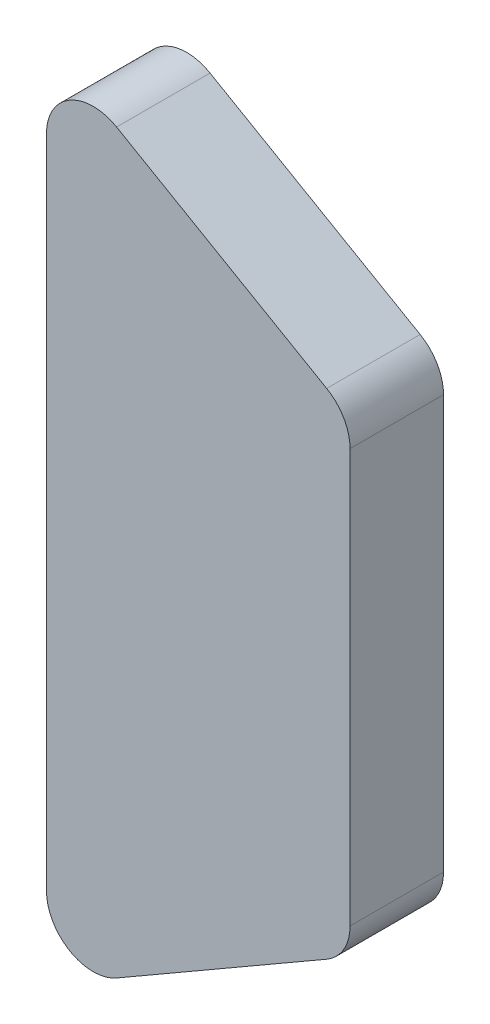
SolidWorks part; units mm, degrees
ref_plane "Ön Düzlem" through (0, 0, 0) normal (0, 0, 1) x (1, 0, 0)
ref_plane "Üst Düzlem" through (0, 0, 0) normal (0, 1, 0) x (1, 0, 0)
ref_plane "Sağ Düzlem" through (0, 0, 0) normal (1, 0, 0) x (0, 0, -1)
sketch "Çizim1" plane through (0, 0, 0) normal (0, 0, 1) x (1, 0, 0)
  line L0 (0, -8.75) -> (0, 8.75)
  line L1 (0, 8.75) -> (6.4952, 5)
  line L2 (6.4952, 5) -> (6.4952, -5)
  line L3 (6.4952, -5) -> (0, -8.75)
  point P4 (0, 0)
  point P5 (6.4952, 0)
  dimension "D1" = 17.5
  dimension "D2" = 10
  dimension "D3" = 7.5
extrude "Yükseklik-Ekstrüzyon1" add sketch "Çizim1" along normal blind 2
fillet "Radyus1" radius 1 4 edges at (0, -8.75, 1) (6.4952, -5, 1) (6.4952, 5, 1) (0, 8.75, 1)
